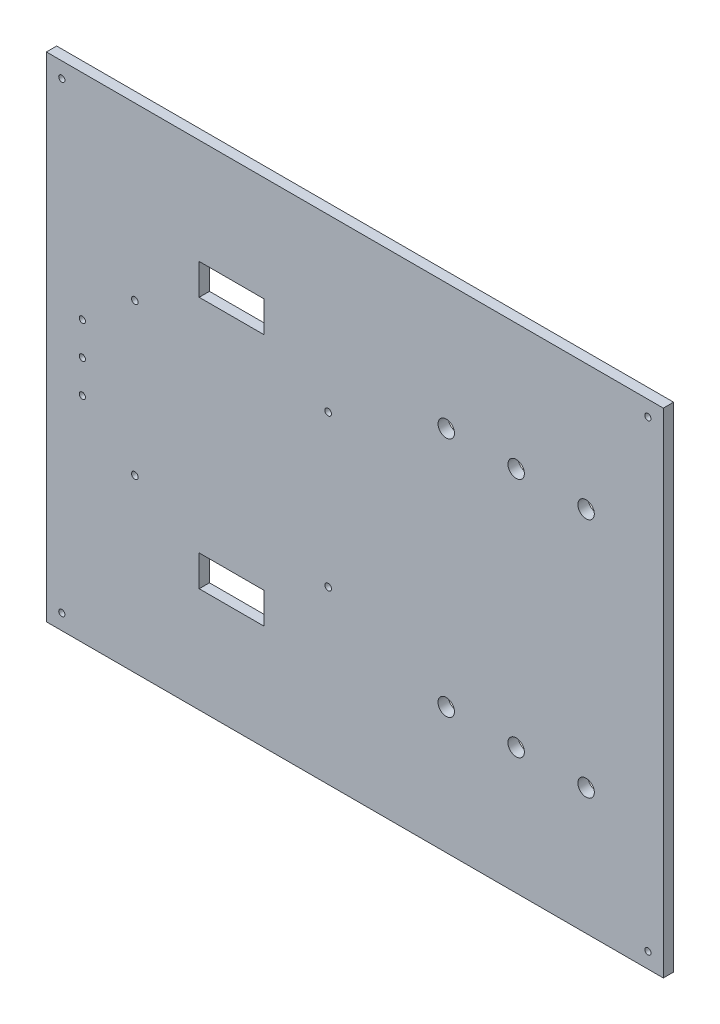
SolidWorks part; units mm, degrees
ref_plane "Front Plane" through (0, 0, 0) normal (0, 0, 1) x (1, 0, 0)
ref_plane "Top Plane" through (0, 0, 0) normal (0, 1, 0) x (1, 0, 0)
ref_plane "Right Plane" through (0, 0, 0) normal (1, 0, 0) x (0, 0, -1)
sketch "Sketch1" plane through (0, 0, 0) normal (0, 0, 1) x (1, 0, 0)
  line L0 (0, 0) -> (300, 0)
  line L1 (300, 0) -> (300, 240)
  line L2 (105.7, 173.83) -> (105.7, 188.92)
  line L3 (300, 120) -> (-69.3523, 120) construction
  line L4 (0, 0) -> (0, 240)
  line L5 (0, 240) -> (300, 240)
  line L9 (105.7, 188.92) -> (74.3, 188.92)
  line L10 (74.3, 173.83) -> (74.3, 188.92)
  line L11 (105.7, 173.83) -> (74.3, 173.83)
  line L12 (105.7, 66.17) -> (74.3, 66.17)
  line L18 (74.3, 66.17) -> (74.3, 51.08)
  line L19 (105.7, 51.08) -> (74.3, 51.08)
  line L20 (105.7, 66.17) -> (105.7, 51.08)
  circle A2 centre (7.5, 232.5) radius 1.5
  circle A3 centre (292.5, 232.5) radius 1.5
  circle A4 centre (292.5, 7.5) radius 1.5
  circle A7 centre (7.5, 7.5) radius 1.5
  circle A13 centre (137, 156.83) radius 1.6
  circle A14 centre (43, 156.83) radius 1.6
  circle A18 centre (43, 83.17) radius 1.6
  circle A19 centre (137, 83.17) radius 1.6
extrude "Boss-Extrude1" add sketch "Sketch1" along normal blind 5
sketch "Sketch3" plane through (0, 0, 5) normal (0, 0, 1) x (1, 0, 0)
  circle A0 centre (17.4848, 136) radius 1.5
  circle A1 centre (17.4848, 120) radius 1.5
  circle A3 centre (17.4848, 104) radius 1.5
extrude "Cut-Extrude1" cut sketch "Sketch3" against normal through all from surface at 0 starting at face at (9, 232.5, 5)
sketch "Sketch5" plane through (0, 0, 5) normal (0, 0, 1) x (1, 0, 0)
  line L0 (300, 120) -> (161.6914, 120)
  line L1 (300, 0) -> (300, 240) construction
  circle A1 centre (194.4424, 178.625) radius 4
  circle A2 centre (228.4424, 178.625) radius 4
  circle A3 centre (262.4424, 178.625) radius 4
extrude "Cut-Extrude3" cut sketch "Sketch5" against normal through all contours A1 | A2 | A3
sketch "Sketch8" plane through (0, 0, 5) normal (0, 0, 1) x (1, 0, 0)
  circle A0 centre (194.4424, 61.375) radius 4
  circle A1 centre (228.4424, 61.375) radius 4
  circle A2 centre (262.4424, 61.375) radius 4
extrude "Cut-Extrude4" cut sketch "Sketch8" against normal through all
